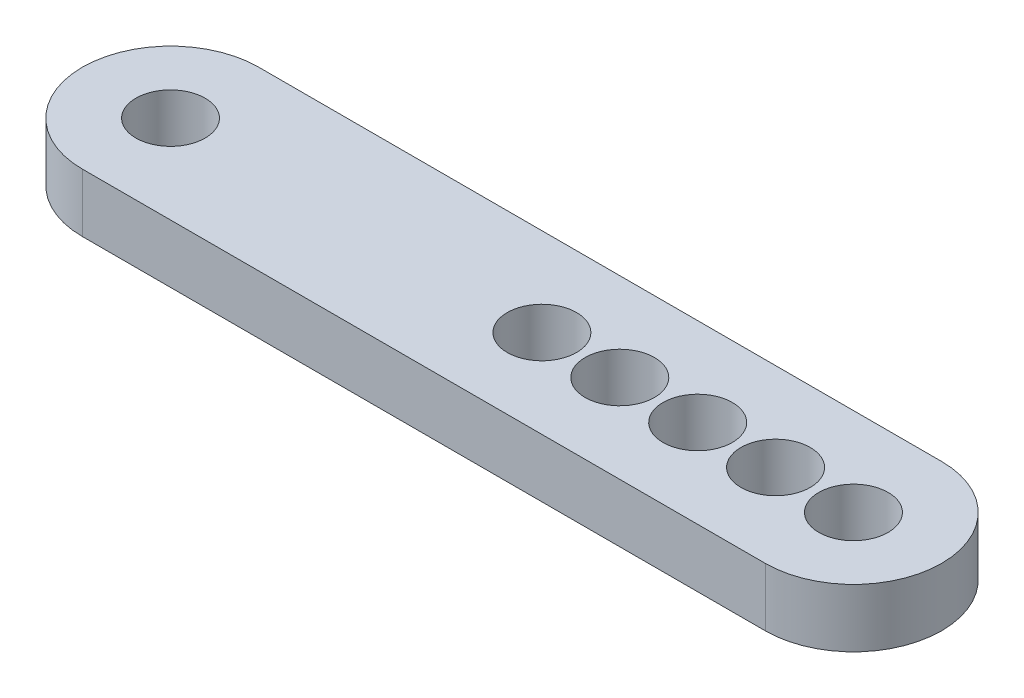
SolidWorks part; units mm, degrees
ref_plane "Front" through (0, 0, 0) normal (0, 0, 1) x (1, 0, 0)
ref_plane "Top" through (0, 0, 0) normal (0, 1, 0) x (1, 0, 0)
ref_plane "Right" through (0, 0, 0) normal (1, 0, 0) x (0, 0, -1)
sketch "Sketch1" plane through (0, 0, 0) normal (0, 1, 0) x (1, 0, 0)
  line L0 (0, 0) -> (35.07, 0) construction
  line L1 (0, 4.53) -> (35.07, 4.53)
  line L2 (0, -4.53) -> (35.07, -4.53)
  arc A0 (0, 4.53) -> (0, -4.53) centre (0, 0) ccw
  arc A1 (35.07, -4.53) -> (35.07, 4.53) centre (35.07, 0) ccw
  circle A2 centre (0, 0) radius 1.778
  circle A3 centre (27.07, 0) radius 1.78
  circle A4 centre (31.07, 0) radius 1.78
  circle A5 centre (35.07, 0) radius 1.78
  circle A6 centre (23.07, 0) radius 1.78
  circle A7 centre (19.07, 0) radius 1.78
  point P3 (17.535, 0)
  point P17 (0, 0)
  point P21 (18.8315, 0)
  point P22 (38.14, 0)
  point P23 (0, 0)
  point P24 (0, 0)
  point P25 (19.07, 0)
  point P26 (0, 0)
  point P27 (0, 0)
  point P28 (19.6909, 0)
  point P29 (35.07, 0)
  point P30 (19.07, 0)
  dimension "D1" = 4.53
  dimension "D2" = 3.556
  dimension "D3" = 27.07
  dimension "D4" = 3.56
  dimension "D6" = 4
  dimension "D8" = 4
  dimension "D5" = 3
  dimension "D7" = 3
extrude "Boss-Extrude1" add sketch "Sketch1" along normal blind 3
